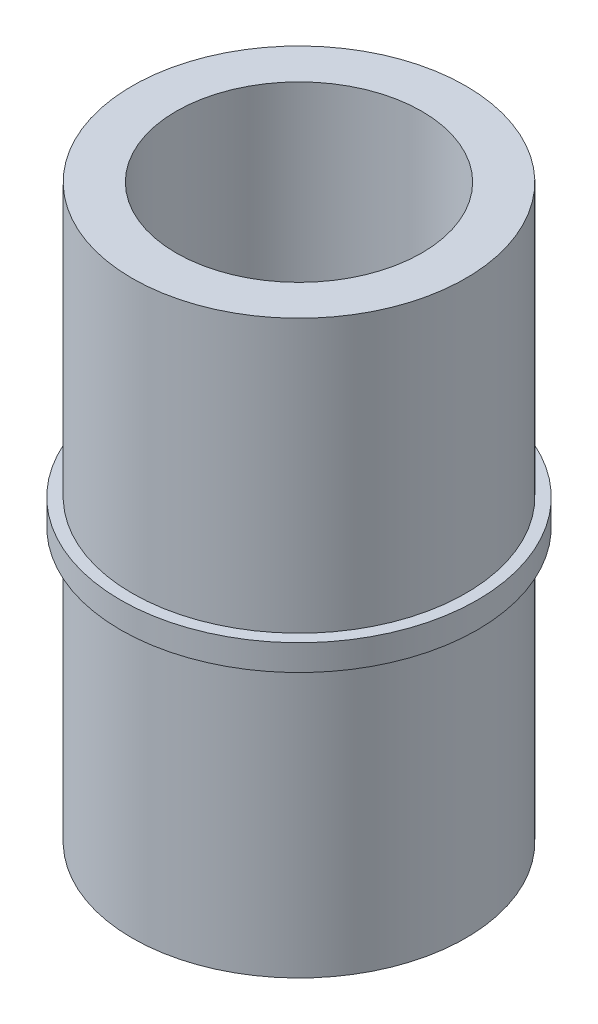
SolidWorks part; units mm, degrees
ref_plane "Front Plane" through (0, 0, 0) normal (0, 0, 1) x (1, 0, 0)
ref_plane "Top Plane" through (0, 0, 0) normal (0, 1, 0) x (1, 0, 0)
ref_plane "Right Plane" through (0, 0, 0) normal (1, 0, 0) x (0, 0, -1)
sketch "Sketch1" plane through (0, 0, 0) normal (0, 0, 1) x (1, 0, 0)
  line L0 (0, -5.6709) -> (0, 4.6369) construction
  line L1 (4.75, -11.05) -> (4.75, 11.05)
  line L2 (4.75, 11.05) -> (6.45, 11.05)
  line L3 (6.45, 11.05) -> (6.45, 0.5)
  line L4 (6.45, 0.5) -> (6.9, 0.5)
  line L5 (6.9, 0.5) -> (6.9, -0.5)
  line L6 (6.9, -0.5) -> (6.45, -0.5)
  line L7 (6.45, -0.5) -> (6.45, -11.05)
  line L8 (6.45, -11.05) -> (4.75, -11.05)
  point P11 (5.0949, -5.726)
  point P12 (6.0586, -0.5986)
  point P13 (4.75, 0)
  point P14 (8.1869, 1.1823)
  dimension "D1" = 9.5
  dimension "D2" = 12.9
  dimension "D3" = 13.8
  dimension "D4" = 1
  dimension "D5" = 22.1
revolve "Revolve1" add sketch "Sketch1" angle 360 about L0
